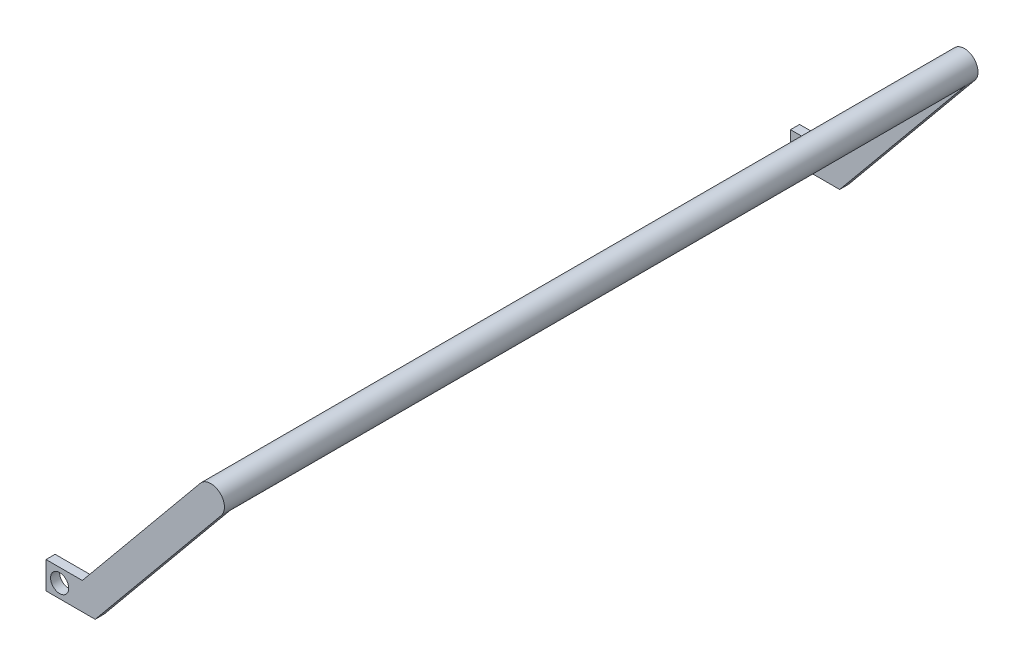
SolidWorks part; units mm, degrees
ref_plane "Front Plane" through (0, 0, 0) normal (0, 0, 1) x (1, 0, 0)
ref_plane "Top Plane" through (0, 0, 0) normal (0, 1, 0) x (1, 0, 0)
ref_plane "Right Plane" through (0, 0, 0) normal (1, 0, 0) x (0, 0, -1)
sketch "Sketch1" plane through (0, 0, 0) normal (0, 0, 1) x (1, 0, 0)
  line L0 (0, 0) -> (20, 0)
  line L1 (20, 0) -> (84.9863, 78.8684)
  line L2 (0, 0) -> (0, -15)
  line L3 (0, -15) -> (27.0764, -15)
  line L4 (27.0764, -15) -> (96.5627, 69.3297)
  line L5 (96.5627, 69.3297) -> (84.9863, 78.8684)
  point P3 (29.4352, -20)
  dimension "D1" = 20
  dimension "D2" = 102.1932
  dimension "D3" = 15
  dimension "D4" = 15
extrude "Boss-Extrude1" add sketch "Sketch1" against normal blind 5
sketch "Sketch2" plane through (0, 0, 0) normal (0, 0, 1) x (1, 0, 0)
  line L0 (96.5627, 69.3297) -> (84.9863, 78.8684) construction
  circle A0 centre (90.7745, 74.0991) radius 7.5
extrude "Boss-Extrude2" add sketch "Sketch2" against normal blind 410
sketch "Sketch3" plane through (0, 0, -410) normal (0, 0, -1) x (-1, 0, 0)
  line L5 (-20, 0) -> (-84.9863, 78.8684)
  line L6 (-96.5627, 69.3297) -> (-27.0764, -15)
  line L7 (-27.0764, -15) -> (0, -15)
  line L8 (0, -15) -> (0, 0)
  line L9 (0, 0) -> (-20, 0)
  line L10 (-20, 0) -> (-84.9863, 78.8684)
  line L11 (-96.5627, 69.3297) -> (-27.0764, -15)
  line L12 (-27.0764, -15) -> (0, -15)
  line L13 (0, -15) -> (0, 0)
  line L14 (0, 0) -> (-20, 0)
  arc A1 (-96.5627, 69.3297) -> (-84.9863, 78.8684) centre (-90.7745, 74.0991) ccw
  arc A2 (-96.5627, 69.3297) -> (-84.9863, 78.8684) centre (-90.7745, 74.0991) ccw
  dimension "D1" = 0
extrude "Boss-Extrude3" add sketch "Sketch3" along normal blind 5 separate body
sketch "Sketch4" plane through (0, 0, -410) normal (0, 0, -1) x (-1, 0, 0)
  circle A1 centre (-90.7745, 74.0991) radius 7.5
  circle A2 centre (-90.7745, 74.0991) radius 7.5
  dimension "D1" = 0
extrude "Boss-Extrude4" add sketch "Sketch4" along normal blind 5
sketch "Sketch5" plane through (0, 0, -415) normal (0, 0, -1) x (-1, 0, 0)
  line L1 (-27.0764, -15) -> (0, -15) construction
  line L2 (0, -15) -> (0, 0) construction
  circle A0 centre (-7.5, -7.5) radius 5
  point P2 (-6.6955, -7.0614)
  point P3 (-7.1143, -7.8862)
  point P4 (0, -7.5)
  dimension "D1" = 10
  dimension "D2" = 7.5
  dimension ".75" = 7.5
extrude "Cut-Extrude1" cut sketch "Sketch5" against normal through all both and the other way through all
